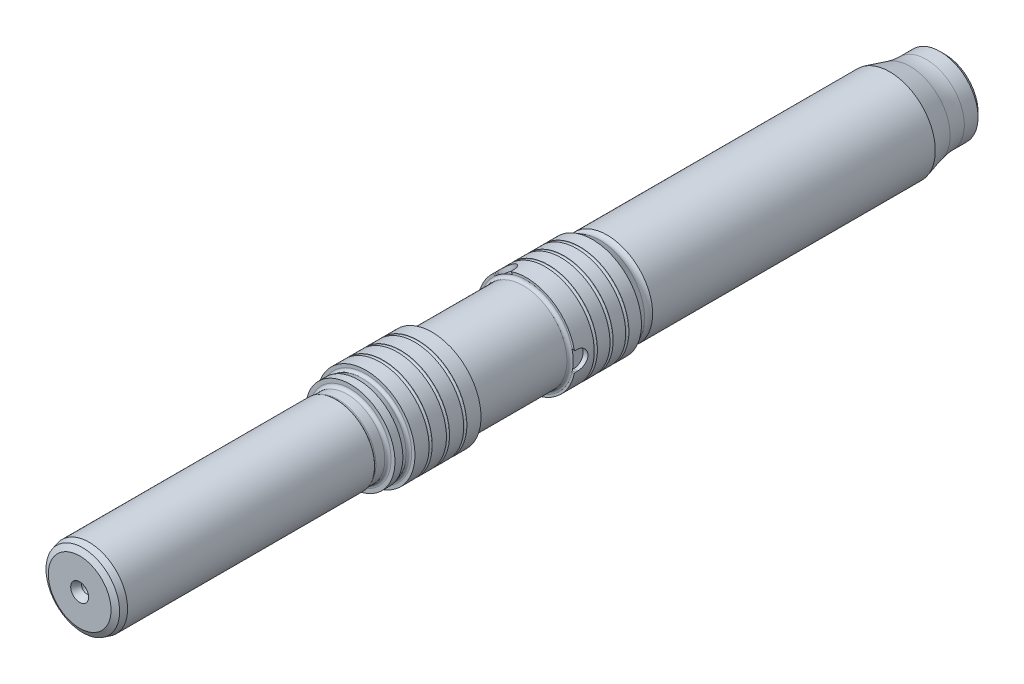
SolidWorks part; units mm, degrees
material "EN39B"
ref_plane "Front Plane" through (0, 0, 0) normal (0, 0, 1) x (1, 0, 0)
ref_plane "Top Plane" through (0, 0, 0) normal (0, 1, 0) x (1, 0, 0)
ref_plane "Right Plane" through (0, 0, 0) normal (1, 0, 0) x (0, 0, -1)
sketch "Sketch1" plane through (0, 0, 0) normal (1, 0, 0) x (0, 0, -1)
  line L0 (0, 0) -> (-275, 0) construction
  line L1 (-17.5, 14.4875) -> (-107.3516, 14.4875)
  line L2 (0, 2.85) -> (0, 10.575)
  line L3 (-274, 11.7016) -> (-275, 9.9696)
  line L4 (-133, 14.875) -> (-133, 15.5775)
  line L5 (-163, 14.875) -> (-163, 15.5775)
  line L6 (-184, 14.55) -> (-184, 15.5775)
  line L7 (-189, 12.9925) -> (-189, 14.2325)
  line L8 (-112, 15.5775) -> (-116, 15.5775)
  line L9 (-163, 15.5775) -> (-167.5, 15.5775)
  line L10 (-184, 0.0483) -> (-184, 31.9032) construction
  line L11 (-163, 0.0483) -> (-163, 31.9032) construction
  line L12 (-189, 0.0483) -> (-189, 31.9032) construction
  line L13 (-133, 0.0483) -> (-133, 31.9032) construction
  line L14 (-272, 12.2375) -> (-274, 11.7016)
  line L15 (0, 15.5775) -> (-275, 15.5775) construction
  line L16 (-193.5, 12.2375) -> (-272, 12.2375)
  line L17 (-134, 13.875) -> (-162, 13.875)
  line L18 (0, 14.4875) -> (-275, 14.4875) construction
  line L19 (-275, 9.9696) -> (-275, 2.85)
  line L20 (0, 13.875) -> (-275, 13.875) construction
  line L21 (0, 12.2375) -> (-275, 12.2375) construction
  line L22 (-186.5, 14.2325) -> (-189, 14.2325)
  line L23 (-190, 11.9925) -> (-192.8443, 11.9925)
  line L24 (-112, 15.5775) -> (-109.6885, 14.2429)
  line L25 (-117, 15.5775) -> (-121, 15.5775)
  line L26 (0, 11.9925) -> (-275, 11.9925) construction
  line L27 (-275, 2.85) -> (-272.7916, 1.575)
  line L28 (-179.5, 15.5775) -> (-179.5, 15.45)
  line L29 (-5.8634, 12.075) -> (-1.5, 12.075)
  line L30 (-178.5, 15.5775) -> (-178.5, 15.45)
  line L31 (-122, 15.5775) -> (-126, 15.5775)
  line L32 (-272.7916, 1.575) -> (-269, 1.575)
  line L33 (-126.5, 14.95) -> (-126.5, 15.45) construction
  line L34 (-179.5, 15.5775) -> (-184, 15.5775)
  line L35 (-174, 15.5775) -> (-174, 15.45)
  line L36 (-121.5, 14.95) -> (-121.5, 15.45) construction
  line L37 (-116.5, 14.95) -> (-116.5, 15.45) construction
  line L38 (-126.5, 14.875) -> (-126.5, 15.5775) construction
  line L39 (-121.5, 14.875) -> (-121.5, 15.5775) construction
  line L40 (-116.5, 14.875) -> (-116.5, 15.5775) construction
  line L41 (-127, 15.5775) -> (-133, 15.5775)
  line L42 (-173, 15.5775) -> (-173, 15.45)
  line L43 (-168.5, 15.5775) -> (-168.5, 15.45)
  line L44 (-167.5, 15.5775) -> (-167.5, 15.45)
  line L45 (-174, 15.5775) -> (-178.5, 15.5775)
  line L46 (-168.5, 15.5775) -> (-173, 15.5775)
  line L47 (-127, 15.45) -> (-127, 15.5775)
  line L48 (-126, 15.45) -> (-126, 15.5775)
  line L49 (-122, 15.45) -> (-122, 15.5775)
  line L50 (-269, 1.575) -> (-268.0536, 0)
  line L51 (0, 2.85) -> (-2.2084, 1.575)
  line L52 (-2.2084, 1.575) -> (-6, 1.575)
  line L53 (-6, 1.575) -> (-6.9464, 0)
  line L54 (-268.0536, 0) -> (-6.9464, 0)
  line L55 (-186.5, 14.2325) -> (-185.0336, 13.7849)
  line L56 (-121, 15.45) -> (-121, 15.5775)
  line L57 (-117, 15.45) -> (-117, 15.5775)
  line L58 (-116, 15.45) -> (-116, 15.5775)
  line L59 (-1.5, 12.075) -> (0, 10.575)
  line L60 (-17.5, 14.4875) -> (-11.0398, 12.7565)
  arc A0 (-193.5, 12.2375) -> (-192.8443, 11.9925) centre (-192.8443, 12.9925) ccw
  arc A1 (-185.0336, 13.7849) -> (-184, 14.55) centre (-184.8, 14.55) ccw
  arc A2 (-189, 12.9925) -> (-190, 11.9925) centre (-190, 12.9925) cw
  arc A3 (-11.0398, 12.7565) -> (-5.8634, 12.075) centre (-5.8634, 32.075) ccw
  arc A4 (-109.6885, 14.2429) -> (-107.3516, 14.4875) centre (-108.6885, 15.975) ccw
  arc A5 (-179.5, 15.45) -> (-178.5, 15.45) centre (-179, 15.45) ccw
  arc A6 (-134, 13.875) -> (-133, 14.875) centre (-134, 14.875) ccw
  arc A7 (-162, 13.875) -> (-163, 14.875) centre (-162, 14.875) cw
  arc A8 (-127, 15.45) -> (-126, 15.45) centre (-126.5, 15.45) ccw
  arc A9 (-122, 15.45) -> (-121, 15.45) centre (-121.5, 15.45) ccw
  arc A10 (-117, 15.45) -> (-116, 15.45) centre (-116.5, 15.45) ccw
  arc A11 (-174, 15.45) -> (-173, 15.45) centre (-173.5, 15.45) ccw
  arc A12 (-168.5, 15.45) -> (-167.5, 15.45) centre (-168, 15.45) ccw
  point P5 (-112, 0)
  point P6 (0, 31.855)
  point P7 (-112, 31.855)
  point P29 (0, 14.23)
  point P30 (-112, 14.485)
  point P32 (-275, 14.23)
  point P42 (-17.5, 0)
  point P45 (0, 12.075)
  point P46 (-275, 12.075)
  point P50 (-17.5, 13.975)
  point P53 (-112, 13.975)
  point P65 (-275, 11.4337)
  point P67 (0, 14.75)
  point P68 (-275, 14.75)
  point P106 (0, 12.075)
  dimension "D8" = 30
  dimension "D9" = 2
  dimension "D10" = 1
  dimension "D30" = 27.5
  dimension "D34" = 2.5
  dimension "D35" = 11.5
  dimension "D38" = 0.5
  dimension "D40" = 29.9
  dimension "D41" = 3.15
  dimension "D42" = 0.5
  dimension "D48" = 16
  dimension "D49" = 29.9
  dimension "D33" = 0.8
  dimension "D16" = 20
  dimension "D43" = 5.7
  dimension "D44" = 86
  dimension "D47" = 1
  dimension "D13" = 15
  dimension "D12" = 24.15
  dimension "D37" = 29.9
  dimension "D39" = 29.9
  dimension "D28" = 1
  dimension "D1" = 275
  dimension "D7" = 28.975
  dimension "D11" = 17.5
  dimension "D14" = 112
  dimension "D15" = 27.95
  dimension "D17" = 31.155
  dimension "D18" = 27.75
  dimension "D19" = 24.475
  dimension "D20" = 15
  dimension "D21" = 3
  dimension "D22" = 1
  dimension "D23" = 45
  dimension "D24" = 21
  dimension "D25" = 6.5
  dimension "D26" = 21
  dimension "D27" = 5
  dimension "D29" = 28.465
  dimension "D31" = 23.985
  dimension "D32" = 4.5
  dimension "D36" = 16.5
  dimension "D45" = 5
  dimension "D46" = 10.5
  dimension "D50" = 3.15
  dimension "D51" = 59
  dimension "D54" = 30
  dimension "D55" = 6
  dimension "D56" = 30
  dimension "D57" = 59
  dimension "D58" = 5.7
  dimension "D60" = 6
  dimension "D62" = 91
revolve "Revolve1" add sketch "Sketch1" angle 360 about L0
ref_plane "Plane2" through (15.5787, 0, 0) normal (1, 0, 0) x (0, 0, -1)
sketch "Sketch3" plane through (15.5787, 0, 0) normal (1, 0, 0) x (0, 0, -1)
  line L1 (-133, 15.5775) -> (-133, -15.5775) construction
  line L2 (-133, 14.875) -> (-133, -14.875) construction
  line L4 (-132, 3) -> (-132.7, 3)
  line L5 (-132.7, -3) -> (-132, -3)
  line L6 (-133, -3.3) -> (-133, 3.3)
  arc A3 (-132, 3) -> (-132, -3) centre (-132, 0) cw
  arc A4 (-132.7, -3) -> (-133, -3.3) centre (-132.7, -3.3) ccw
  arc A5 (-132.7, 3) -> (-133, 3.3) centre (-132.7, 3.3) cw
  point P16 (-133, 0)
  dimension "D2" = 3
  dimension "D3" = 4
  dimension "D1" = 0.3
  dimension "D4" = 0.3
  dimension "D5" = 6.6
extrude "Cut-Extrude1" cut sketch "Sketch3" against normal blind 1.55
pattern_circular "CirPattern1" count 3 over 360 about axis through (0, 0, 0) along (0, 0, 1) of "Cut-Extrude1"
